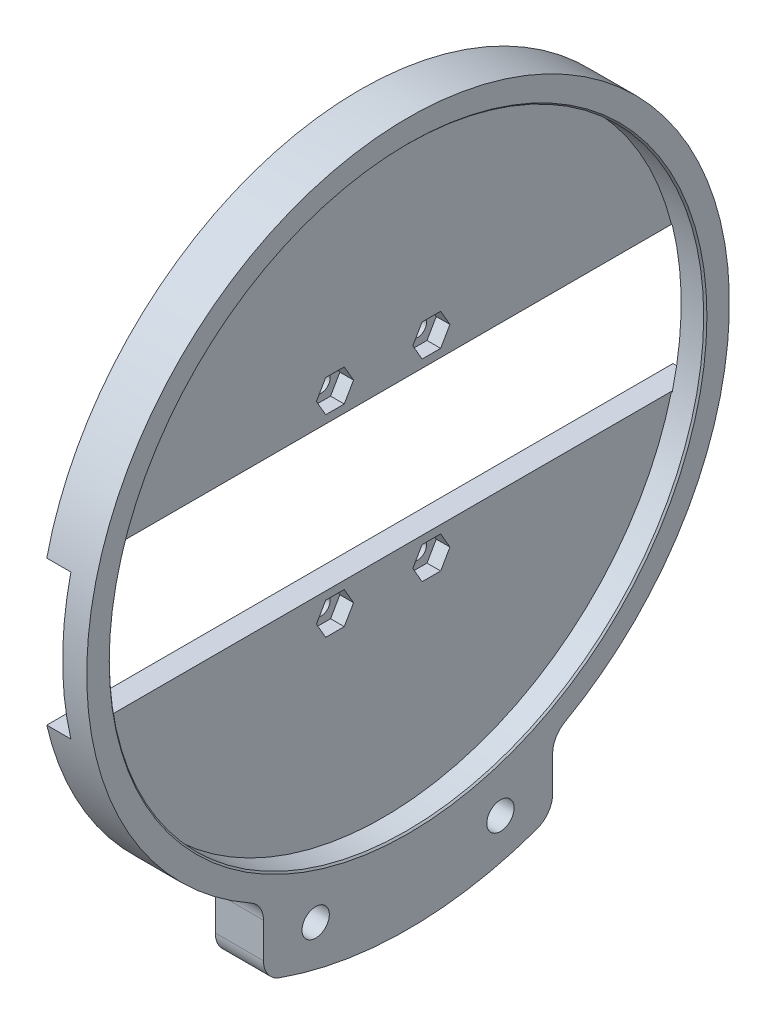
SolidWorks part; units mm, degrees
material "ABS"
ref_plane "Спереди" through (0, 0, 0) normal (0, 0, 1) x (1, 0, 0)
ref_plane "Сверху" through (0, 0, 0) normal (0, 1, 0) x (1, 0, 0)
ref_plane "Справа" through (0, 0, 0) normal (1, 0, 0) x (0, 0, -1)
sketch "Эскиз1" plane through (0, 0, 0) normal (0, 0, 1) x (1, 0, 0)
  line L0 (-5.8819, 0) -> (8.2434, 0) construction
  line L1 (6, 37) -> (2.9, 37)
  line L2 (0, 0) -> (2.9, 0)
  line L3 (0, 0) -> (0, 47.5)
  line L4 (0, 47.5) -> (6, 47.5)
  line L5 (6, 37) -> (6, 47.5)
  line L6 (2.9, 37) -> (2.9, 0)
  dimension "D1" = 95
  dimension "D2" = 74
  dimension "D3" = 3.1
  dimension "D4" = 6
revolve "Повернуть1" add sketch "Эскиз1" angle 360 about L0
chamfer "Фаска2" distance 0.2 angle 45 1 edges at (6, 0, 37)
sketch "Эскиз2" plane through (0, 0, 0) normal (-1, 0, 0) x (0, 0, 1)
  line L0 (-18, -35.7211) -> (-18, -43.9574)
  line L1 (0, -10.9094) -> (0, -21.9777) construction
  line L2 (18, -35.7211) -> (18, -43.9574)
  circle A0 centre (0, 0) radius 47.5 construction
  arc A1 (18, -43.9574) -> (-18, -43.9574) centre (0, 0) ccw
  arc A2 (18, -35.7211) -> (-18, -35.7211) centre (0, 0) ccw
  dimension "D1" = 80
  dimension "D2" = 36
extrude "Вырез-Вытянуть1" cut sketch "Эскиз2" against normal blind 10
hole_wizard "Зенковка для винта с потайной головкой M31" positions "Эскиз4" profile "Эскиз3" countersink size "M3" standard "ISO" end condition through all
sketch "Эскиз4" plane through (0, 0, 0) normal (-1, 0, 0) x (0, 0, 1)
  line L0 (0, 31.2186) -> (0, 16.1203) construction
  point P0 (-11.5, -41)
  point P8 (11.5, -41)
  dimension "D1" = 41
  dimension "D2" = 11.5
sketch "Эскиз3" plane through (0, -41, -11.5) normal (0, 1, 0) x (0, 0, 1)
  line L0 (0, 0) -> (0, 6)
  line L1 (0, 6) -> (1.7, 6)
  line L2 (1.7, 6) -> (1.7, 1.45)
  line L3 (1.7, 1.45) -> (3.15, 0)
  line L5 (3.15, 0) -> (0, 0)
  line L6 (-1.7, 1.45) -> (-3.15, 0) construction
  line L11 (0, -6.35) -> (0, 107.95) construction
  dimension "Диаметр сквозного отверстия" = 3.4
  dimension "Глубина сквозного отверстия" = 6
  dimension "Диаметр передней зенковки" = 6.3
  dimension "Угол передней зенковки" = 90
fillet "Скругление1" radius 3 4 edges at (3, -43.9574, 18) (3, -43.9574, -18) (3, -35.7211, -18) (3, -35.7211, 18)
sketch "Эскиз5" plane through (0, 0, 0) normal (-1, 0, 0) x (0, 0, 1)
  line L1 (-40, 9) -> (40, 9)
  line L2 (-40, 9) -> (-40, -9)
  line L3 (-40, -9) -> (40, -9)
  line L4 (40, 9) -> (40, -9)
  line L5 (-40, 9) -> (40, -9) construction
  line L6 (-40, -9) -> (40, 9) construction
  arc A0 (19.5349, -34.9054) -> (-19.5349, -34.9054) centre (0, 0) ccw construction
  point P0 (0, 0)
  dimension "D1" = 18
extrude "Вырез-Вытянуть2" cut sketch "Эскиз5" against normal blind 3
hole_wizard "Отверстие с зазором M21" positions "Эскиз7" profile "Эскиз6" hole size "M2" standard "ISO" end condition through all
sketch "Эскиз7" plane through (0, 0, 0) normal (-1, 0, 0) x (0, 0, 1)
  line L0 (-37, 0) -> (37, 0) construction
  line L2 (0, 9) -> (0, -9) construction
  line L3 (38.9744, 9) -> (-38.9744, 9) construction
  line L4 (-38.9744, -9) -> (38.9744, -9) construction
  arc A0 (-35.8887, 9) -> (-35.8887, -9) centre (0, 0) ccw construction
  arc A1 (35.8887, -9) -> (35.8887, 9) centre (0, 0) ccw construction
  point P0 (6, 12)
  point P19 (-6, 12)
  point P20 (-6, -12)
  point P21 (6, -12)
  dimension "D1" = 12
  dimension "D2" = 24
sketch "Эскиз6" plane through (0, 12, 6) normal (0, 1, 0) x (0, 0, 1)
  line L0 (0, 0) -> (0, 6)
  line L1 (0, 6) -> (1.1, 6)
  line L2 (1.1, 6) -> (1.1, 0)
  line L5 (1.1, 0) -> (0, 0)
  line L11 (0, -6.35) -> (0, 107.95) construction
  dimension "Диаметр сквозного отверстия" = 2.2
  dimension "Глубина сквозного отверстия" = 6
sketch "Эскиз8" plane through (2.9, 0, 0) normal (1, 0, 0) x (0, 0, -1)
  line L1 (7.1547, 10) -> (8.3094, 12)
  line L2 (8.3094, 12) -> (7.1547, 14)
  line L3 (7.1547, 14) -> (4.8453, 14)
  line L4 (4.8453, 14) -> (3.6906, 12)
  line L5 (3.6906, 12) -> (4.8453, 10)
  line L6 (4.8453, 10) -> (7.1547, 10)
  line L7 (-4.8453, 10) -> (-3.6906, 12)
  line L8 (-3.6906, 12) -> (-4.8453, 14)
  line L9 (-4.8453, 14) -> (-7.1547, 14)
  line L10 (-7.1547, 14) -> (-8.3094, 12)
  line L11 (-8.3094, 12) -> (-7.1547, 10)
  line L12 (-7.1547, 10) -> (-4.8453, 10)
  line L13 (-4.8453, -14) -> (-3.6906, -12)
  line L14 (-3.6906, -12) -> (-4.8453, -10)
  line L15 (-4.8453, -10) -> (-7.1547, -10)
  line L16 (-7.1547, -10) -> (-8.3094, -12)
  line L17 (-8.3094, -12) -> (-7.1547, -14)
  line L18 (-7.1547, -14) -> (-4.8453, -14)
  line L19 (7.1547, -14) -> (8.3094, -12)
  line L20 (8.3094, -12) -> (7.1547, -10)
  line L21 (7.1547, -10) -> (4.8453, -10)
  line L22 (4.8453, -10) -> (3.6906, -12)
  line L23 (3.6906, -12) -> (4.8453, -14)
  line L24 (4.8453, -14) -> (7.1547, -14)
  circle A0 centre (6, 12) radius 2 construction
  circle A1 centre (-6, 12) radius 2 construction
  circle A2 centre (-6, -12) radius 2 construction
  circle A3 centre (6, -12) radius 2 construction
  dimension "D1" = 4
extrude "Вырез-Вытянуть3" cut sketch "Эскиз8" against normal blind 1.7
